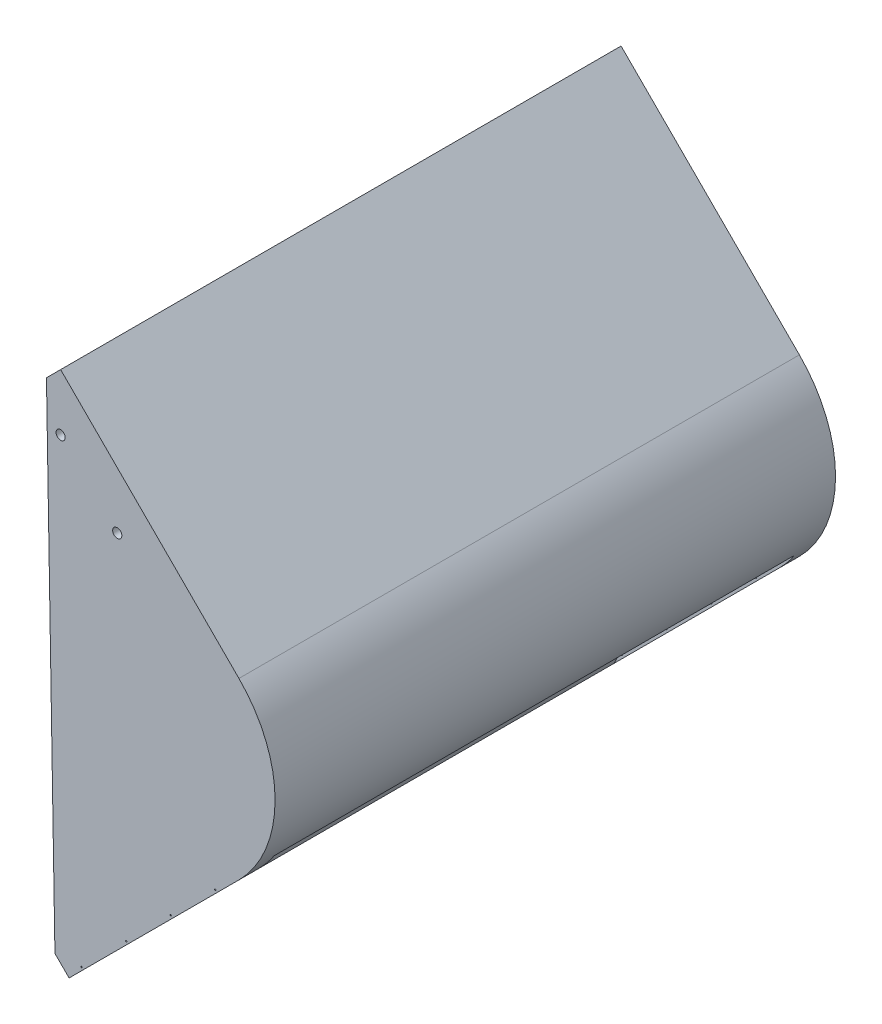
SolidWorks part; units mm, degrees
material "ABS"
ref_plane "Front Plane" through (0, 0, 0) normal (0, 0, 1) x (1, 0, 0)
ref_plane "Top Plane" through (0, 0, 0) normal (0, 1, 0) x (1, 0, 0)
ref_plane "Right Plane" through (0, 0, 0) normal (1, 0, 0) x (0, 0, -1)
sketch "Sketch1" plane through (0, 0, 0) normal (0, 0, 1) x (1, 0, 0)
  line L0 (0, 34.1531) -> (0, -57.4199) construction
  line L5 (-38.8492, 0) -> (36.928, 0) construction
  line L6 (0, 12.9127) -> (-56.5685, 69.4813)
  line L7 (0, -42.4534) -> (-53.8815, -96.3349)
  line L8 (-4.4901, -37.9632) -> (-58.3717, -91.8448)
  line L9 (-4.4901, 8.4226) -> (-61.0587, 64.9911)
  line L10 (-58.3717, -91.8448) -> (-53.8815, -96.3349)
  line L11 (-61.0587, 64.9911) -> (-56.5685, 69.4813)
  arc A1 (0, 12.9127) -> (0, -42.4534) centre (-27.683, -14.7703) cw
  arc A2 (-4.4901, 8.4226) -> (-4.4901, -37.9632) centre (-27.683, -14.7703) cw
  dimension "D1" = 45
  dimension "D2" = 6.35
  dimension "D3" = 76.2
  dimension "D4" = 80
extrude "Boss-Extrude1" add sketch "Sketch1" along normal blind 177.8
sketch "Sketch2" plane through (0, 0, 0) normal (0, 0, -1) x (-1, 0, 0)
  line L0 (61.0587, 64.9911) -> (58.3717, -91.8448)
  line L5 (4.4901, 8.4226) -> (61.0587, 64.9911)
  line L6 (0, -42.4534) -> (53.8815, -96.3349)
  line L7 (53.8815, -96.3349) -> (58.3717, -91.8448)
  line L8 (58.3717, -91.8448) -> (4.4901, -37.9632)
  line L12 (0, -42.4534) -> (53.8815, -96.3349)
  line L13 (53.8815, -96.3349) -> (58.3717, -91.8448)
  line L14 (58.3717, -91.8448) -> (4.4901, -37.9632)
  line L18 (4.4901, 8.4226) -> (61.0587, 64.9911)
  line L19 (61.0587, 64.9911) -> (56.5685, 69.4813)
  line L20 (61.0587, 64.9911) -> (56.5685, 69.4813)
  line L21 (56.5685, 69.4813) -> (0, 12.9127)
  line L22 (56.5685, 69.4813) -> (0, 12.9127)
  arc A2 (0, 12.9127) -> (0, -42.4534) centre (27.683, -14.7703) ccw
  arc A3 (4.4901, 8.4226) -> (4.4901, -37.9632) centre (27.683, -14.7703) ccw
  arc A4 (0, 12.9127) -> (0, -42.4534) centre (27.683, -14.7703) ccw
  arc A5 (4.4901, 8.4226) -> (4.4901, -37.9632) centre (27.683, -14.7703) ccw
  line M12 (58.3717, -91.8448) -> (4.4901, -37.9632)
  arc M13 (4.4901, -37.9632) -> (4.4901, 8.4226) centre (27.683, -14.7703) cw
  line M14 (4.4901, 8.4226) -> (61.0587, 64.9911)
  dimension "D1" = 0
extrude "Boss-Extrude2" add sketch "Sketch2" against normal blind 6.35 contours L0 M14 M13 M12
sketch "Sketch4" plane through (0, 0, 177.8) normal (0, 0, 1) x (1, 0, 0)
  line L3 (-61.0587, 64.9911) -> (-58.3717, -91.8448)
  line L4 (-58.3717, -91.8448) -> (-4.4901, -37.9632)
  line L5 (-58.3717, -91.8448) -> (-4.4901, -37.9632)
  line L6 (0, 12.9127) -> (-56.5685, 69.4813)
  line L7 (0, 12.9127) -> (-56.5685, 69.4813)
  line L9 (-4.4901, -37.9632) -> (-58.3717, -91.8448)
  line L10 (-58.3717, -91.8448) -> (-53.8815, -96.3349)
  line L11 (-53.8815, -96.3349) -> (0, -42.4534)
  line L15 (-4.4901, -37.9632) -> (-58.3717, -91.8448)
  line L16 (-58.3717, -91.8448) -> (-53.8815, -96.3349)
  line L17 (-53.8815, -96.3349) -> (0, -42.4534)
  line L18 (-61.0587, 64.9911) -> (-58.3717, -91.8448)
  line L19 (-4.4901, 8.4226) -> (-61.0587, 64.9911)
  line L20 (-4.4901, 8.4226) -> (-61.0587, 64.9911)
  line L23 (-56.5685, 69.4813) -> (-61.0587, 64.9911)
  line L24 (-56.5685, 69.4813) -> (-61.0587, 64.9911)
  line L25 (-61.0587, 64.9911) -> (-4.4901, 8.4226)
  line L26 (-61.0587, 64.9911) -> (-4.4901, 8.4226)
  arc A1 (-4.4901, -37.9632) -> (-4.4901, 8.4226) centre (-27.683, -14.7703) ccw
  arc A2 (0, -42.4534) -> (0, 12.9127) centre (-27.683, -14.7703) ccw
  arc A3 (-4.4901, -37.9632) -> (-4.4901, 8.4226) centre (-27.683, -14.7703) ccw
  arc A4 (0, -42.4534) -> (0, 12.9127) centre (-27.683, -14.7703) ccw
  arc A5 (-4.4901, -37.9632) -> (-4.4901, 8.4226) centre (-27.683, -14.7703) ccw
  arc A6 (-4.4901, -37.9632) -> (-4.4901, 8.4226) centre (-27.683, -14.7703) ccw
  line M16 (-61.0587, 64.9911) -> (-4.4901, 8.4226)
  arc M17 (-4.4901, 8.4226) -> (-4.4901, -37.9632) centre (-27.683, -14.7703) cw
  line M18 (-4.4901, -37.9632) -> (-58.3717, -91.8448)
  dimension "D1" = 0
  dimension "D2" = 0
extrude "Boss-Extrude3" add sketch "Sketch4" against normal blind 6.35 contours L18 M16 M18 M17
sketch "Sketch5" plane through (21.2267, -21.2267, 0) normal (0.7071, -0.7071, 0) x (0.7071, 0.7071, 0)
  line L1 (-22.3991, 6.35) -> (-104.2191, 6.35)
  line L2 (-22.3991, 6.35) -> (-22.3991, 171.45)
  line L3 (-22.3991, 171.45) -> (-104.2191, 171.45)
  line L4 (-106.2191, 0) -> (-30.0191, 0)
  line L5 (-30.0191, 0) -> (-30.0191, 177.8)
  line L6 (-30.0191, 177.8) -> (-106.2191, 177.8)
  line L7 (-106.2191, 177.8) -> (-106.2191, 0)
  line L8 (-106.2191, 0) -> (-30.0191, 0)
  line L9 (-30.0191, 0) -> (-30.0191, 177.8)
  line L10 (-30.0191, 177.8) -> (-106.2191, 177.8)
  line L11 (-106.2191, 177.8) -> (-106.2191, 0)
  line L12 (-104.2191, 6.35) -> (-104.2191, 171.45)
  dimension "D2" = 7.62
  dimension "D3" = 6.35
  dimension "D4" = 6.35
  dimension "D5" = 2
  dimension "D1" = 0
extrude "Cut-Extrude1" cut sketch "Sketch5" against normal through all contours L2 L1 L12 L3
sketch "Sketch8" plane through (0, 0, 6.35) normal (0, 0, 1) x (1, 0, 0)
  line L0 (-52.4673, -94.9207) -> (-46.353, -82.9207)
  line L1 (-56.9575, -90.4306) -> (-50.8431, -78.4306)
  line L2 (-50.8431, -78.4306) -> (-46.353, -82.9207)
  line L7 (-61.0587, 64.9911) -> (-58.3717, -91.8448)
  line L8 (-58.3717, -91.8448) -> (-56.9575, -90.4306)
  line L9 (-56.9575, -90.4306) -> (-52.4673, -94.9207)
  line L10 (-52.4673, -94.9207) -> (0, -42.4534)
  line L11 (4.8587, -36.5358) -> (0.2635, -31.9405)
  line L13 (-4.4901, 8.4226) -> (-61.0587, 64.9911)
  line L14 (-61.0587, 64.9911) -> (-58.3717, -91.8448)
  line L15 (-58.3717, -91.8448) -> (-56.9575, -90.4306)
  line L16 (-56.9575, -90.4306) -> (-52.4673, -94.9207)
  line L17 (-52.4673, -94.9207) -> (0, -42.4534)
  line L18 (4.8587, -36.5358) -> (0.2635, -31.9405)
  line L20 (-4.4901, 8.4226) -> (-61.0587, 64.9911)
  arc A1 (0.2635, -31.9405) -> (-4.4901, 8.4226) centre (-27.683, -14.7703) ccw
  arc A2 (0.2635, -31.9405) -> (-4.4901, 8.4226) centre (-27.683, -14.7703) ccw
  arc A4 (0, -42.4534) -> (4.8587, -36.5358) centre (-27.683, -14.7703) ccw
  arc A5 (0, -42.4534) -> (4.8587, -36.5358) centre (-27.683, -14.7703) ccw
  line M14 (-56.9575, -90.4306) -> (-52.4673, -94.9207)
  dimension "D2" = 18
  dimension "D3" = 12
  dimension "D1" = 0
extrude "Boss-Extrude6" add sketch "Sketch8" along normal up to surface (165.1 mm away) contours L2 L1 L0 M14 up to face at (-27.6341, -39.2508, 171.45)
sketch "Sketch9" plane through (0, 0, 177.8) normal (0, 0, 1) x (1, 0, 0)
  line L0 (0, 12.9127) -> (-56.5685, 69.4813) construction
  line L1 (-56.5685, 69.4813) -> (-61.0587, 64.9911) construction
  circle A0 centre (-56.5685, 51.5208) radius 1.4605
  circle A1 centre (-38.608, 33.5602) radius 1.4605
  dimension "D1" = 2.921
  dimension "D2" = 2.921
  dimension "D3" = 12.7
  dimension "D4" = 12.7
  dimension "D5" = 12.7
  dimension "D6" = 38.1
extrude "Cut-Extrude2" cut sketch "Sketch9" against normal through all both and the other way through all
sketch "Sketch10" plane through (0, 0, 0) normal (0, 0, -1) x (-1, 0, 0)
  line L0 (58.3717, -91.8448) -> (53.8815, -96.3349) construction
  line L1 (53.8815, -96.3349) -> (0, -42.4534) construction
  circle A0 centre (49.9302, -91.306) radius 0.2159
  circle A1 centre (35.7881, -77.1638) radius 0.2159
  circle A2 centre (21.646, -63.0217) radius 0.2159
  circle A3 centre (7.5038, -48.8796) radius 0.2159
  circle A4 centre (-6.6383, -34.7374) radius 0.2159
  dimension "D1" = 0.4318
  dimension "D2" = 0.4318
  dimension "D6" = 0.4318
  dimension "D9" = 0.4318
  dimension "D12" = 0.4318
  dimension "0.3" = 6.35
  dimension "D3" = 0.762
  dimension "D4" = 20
  dimension "D5" = 0.762
  dimension "D7" = 20
  dimension "D8" = 0.762
  dimension "D10" = 20
  dimension "D11" = 0.762
  dimension "D13" = 20
  dimension "D14" = 0.762
extrude "Cut-Extrude3" cut sketch "Sketch10" against normal through all
